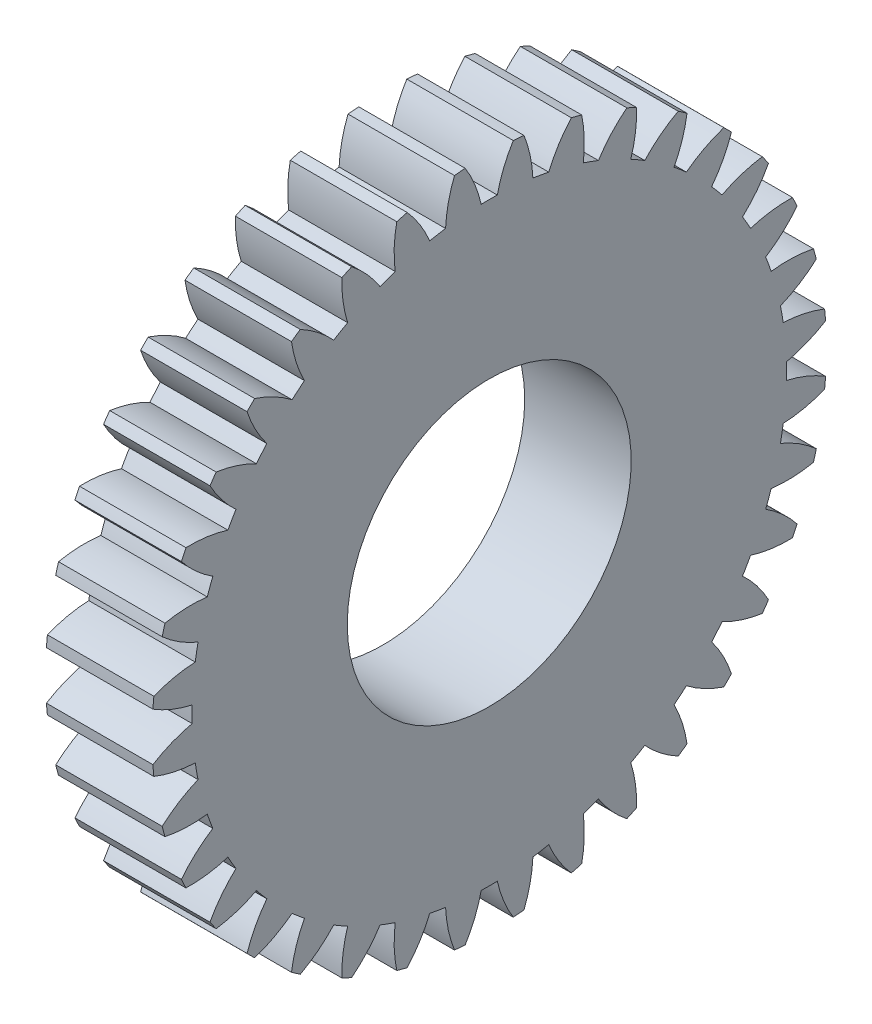
SolidWorks part; units mm, degrees
ref_plane "Plane1" through (0, 0, 0) normal (0, 0, 1) x (1, 0, 0)
ref_plane "Plane2" through (0, 0, 0) normal (0, 1, 0) x (1, 0, 0)
ref_plane "Plane3" through (0, 0, 0) normal (1, 0, 0) x (0, 0, -1)
sketch "HoldingSke" plane through (0, 0, 0) normal (0, 1, 0) x (1, 0, 0)
  line L0 (0, 0) -> (1.618, -1.1756)
  line L1 (-15, 0) -> (100, 0) construction
  line L2 (0, 0) -> (-2.1039, 2.3779)
  line L3 (0, 0) -> (-11.863, 4.5341)
  line L4 (0, 0) -> (6.9867, 5.0761)
  line L5 (0, 0) -> (-46.8476, -17.4728)
  line L6 (0, 0) -> (-2.4869, -1.6779)
  line L7 (-2.1039, 2.3779) -> (8.6586, 51.2059)
  line L8 (-76.2, 54.61) -> (-74.8, 54.61)
  line L9 (-71.009, 38.7566) -> (-53.1078, 45.2721)
  line L10 (-76.2, 71.12) -> (104.1128, 71.12)
  line L11 (0, 0) -> (-3, 0)
  line L12 (-76.2, 101.6) -> (-76.181, 101.6)
  line L13 (24.9733, 27.94) -> (52.9518, 28.4284)
  line L14 (24.9733, 27.94) -> (24.9743, 27.94)
  line L15 (24.9733, 27.94) -> (100.4006, 29.5858)
  line L16 (-63.627, -0.5) -> (-12.827, -0.5)
  circle A0 centre (0, 0) radius 4.5
  circle A1 centre (0, 0) radius 8.374
  circle A2 centre (0, 0) radius 37.5
  circle A3 centre (0, 0) radius 4.5
  dimension "MHD" = 16.748
  dimension "Hub_dia" = 75
  dimension "Bore" = 9
  dimension "MBD" = 9
  dimension "Num_teeth" = 36
  dimension "Pitch" = 2
  dimension "Overall_len" = 50
  dimension "Show_teeth" = 36
  dimension "Thickness" = 3
  dimension "OAL" = 50.0001
  dimension "T_dim" = 1.4
  dimension "Ap" = 20
  dimension "H" = 19.05
  dimension "Pitch_radius" = 180.3128
  dimension "Width" = 3
  dimension "Backlash" = 0.019
  dimension "Addendum_fac" = 1
  dimension "Dedendum_fac" = 1.25
  dimension "Clearance_fac" = 0.25
  dimension "Dedendum_add" = 0.001
  dimension "Module" = 0.5
sketch "BasProSke" plane through (0, 0, 0) normal (0, 1, 0) x (1, 0, 0)
  line L0 (-10, 0) -> (60, 0) construction
  line L1 (0, 0) -> (0, 9.5)
  line L2 (0, 0) -> (3, 0)
  line L3 (3, 0) -> (3, 9.5)
  line L4 (3, 9.5) -> (0, 9.5)
  dimension "Thickness" = 3
  dimension "Diameter" = 19
revolve "Base-Revolve" add sketch "BasProSke" angle 360 about L0
sketch "TooCutSke" plane through (0, 0, 0) normal (1, 0, 0) x (0, 0, -1)
  line L1 (0, 0) -> (0, 107) construction
  line L2 (0, 0) -> (-0.4258, 8.9899) construction
  line L3 (0, 0) -> (-1.5676, 17.9172) construction
  line L4 (-0.4258, 8.9899) -> (-0.7838, 8.9586) construction
  arc A0 (0.2272, 8.3709) -> (-0.2272, 8.3709) centre (0, 0) ccw
  arc A1 (0.6921, 9.5002) -> (-0.6921, 9.5002) centre (0, 0) ccw
  circle A2 centre (0, 0) radius 9 construction
  circle A3 centre (0, 0) radius 8.4572 construction
  arc A4 (-0.2272, 8.3709) -> (-0.6921, 9.5002) centre (-3.7404, 7.5851) ccw
  arc A5 (0.6921, 9.5002) -> (0.2272, 8.3709) centre (3.7404, 7.5851) ccw
  dimension "Root_dia" = 16.748
  dimension "Overcut_dia" = 19.0508
  dimension "Pitch_dia" = 18
  dimension "Base_dia" = 16.9145
  dimension "Flank_rad" = 3.6
  dimension "Half_ang" = 5
  dimension "Half_CT" = 0.3593
extrude "ToothCut" cut sketch "TooCutSke" along normal through all
fillet "Breaks" [suppressed] radius 0.01
fillet "RootFillets" [suppressed] radius 0.126
pattern_circular "TeethCuts" count 36 every 10 about axis through (-10, 0, 0) along (1, 0, 0) of "ToothCut", "RootFillets", "Breaks"
sketch "HubNeaOneSke" plane through (0, 0, 0) normal (-1, 0, 0) x (0, 0, 1)
  circle A0 centre (0, 0) radius 8.374
  dimension "Diameter" = 16.748
extrude "HubNearOne" [suppressed] add sketch "HubNeaOneSke" along normal blind 47.0001
sketch "HubNeaBotSke" plane through (0, 0, 0) normal (-1, 0, 0) x (0, 0, 1)
  circle A0 centre (0, 0) radius 8.374
  dimension "Diameter" = 16.748
extrude "HubNearBoth" [suppressed] add sketch "HubNeaBotSke" along normal blind 23.5
ref_plane "FarPln" through (3, 0, 0) normal (1, 0, 0) x (0, 0, -1)
sketch "HubFarSke" plane through (3, 0, 0) normal (1, 0, 0) x (0, 0, -1)
  circle A0 centre (0, 0) radius 8.374
  dimension "Diameter" = 16.748
extrude "HubFar" [suppressed] add sketch "HubFarSke" along normal blind 23.5
sketch "BorSke" plane through (0, 0, 0) normal (1, 0, 0) x (0, 0, -1)
  circle A0 centre (0, 0) radius 4
  dimension "Diameter" = 8
extrude "Bore" cut sketch "BorSke" along normal mid plane 100.0001
sketch "KeySke" plane through (0, 0, 0) normal (1, 0, 0) x (0, 0, -1)
  line L0 (-1.5, 0) -> (-1.5, 5.9)
  line L1 (-1.5, 5.9) -> (1.5, 5.9)
  line L2 (1.5, 5.9) -> (1.5, 0)
  line L3 (0, 0) -> (0, 34) construction
  line L4 (-1.5, 0) -> (1.5, 0)
  dimension "Width" = 3
  dimension "Offset" = 5.9
extrude "Keyway" [suppressed] cut sketch "KeySke" along normal mid plane 100.0001
pattern_circular "Keyway2" [suppressed] count 2 every 90 about axis through (-10, 0, 0) along (1, 0, 0)
equation "' \"Module@HoldingSke\" = 6.35"
equation "' \"Num_teeth@HoldingSke\" = 12"
equation "' \"Ap@HoldingSke\" =  20"
equation "' \"Ap@HoldingSke\" = 20"
equation "' \"Width@HoldingSke\" = 0.5 * 25.4"
equation "' \"Hub_dia@HoldingSke\"= 1 * 25.4"
equation "' \"Hub_dia@HoldingSke\" = 1 * 25.4"
equation "' \"Overall_len@HoldingSke\" = 1.0 * 25.4"
equation "' \"Bore@HoldingSke\" = 0.75 * 25.4"
equation "' \"T_dim@HoldingSke\" = 0.1 * 25.4"
equation "' \"Width@KeySke\" = 0.25 * 25.4"
equation "' \"Show_teeth@HoldingSke\" = 13"
equation "' \"Backlash@HoldingSke\" = 0.009 * 25.4"
equation "' \"Addendum_fac@HoldingSke\" = 1.0"
equation "' \"Dedendum_fac@HoldingSke\" = 1.25"
equation "' \"Dedendum_add@HoldingSke\" = 0.00005 * 25.4"
equation "' \"Clearance_fac@HoldingSke\" = 0.25"
equation "\"Pitch@HoldingSke\" = 1 / \"Module@HoldingSke\""
equation "\"Overcut_dia@TooCutSke\" = (\"Num_teeth@HoldingSke\" + 2 * \"Addendum_fac@HoldingSke\") / \"Pitch@HoldingSke\" + 0.002 * 25.4"
equation "\"Pitch_dia@TooCutSke\" = \"Num_teeth@HoldingSke\" / \"Pitch@HoldingSke\""
equation "\"Base_dia@TooCutSke\" = \"Num_teeth@HoldingSke\" / \"Pitch@HoldingSke\" * cos((\"Ap@HoldingSke\"  * 3.14159265 / 180))"
equation "\"Root_dia@TooCutSke\" = (\"Num_teeth@HoldingSke\" + 2) / \"Pitch@HoldingSke\" - 2 * (\"Addendum_fac@HoldingSke\" + \"Dedendum_fac@HoldingSke\") / \"Pitch@HoldingSke\" - \"Dedendum_add@HoldingSke\" * 2"
equation "\"Half_ang@TooCutSke\" = 180 / \"Num_teeth@HoldingSke\""
equation "\"Half_CT@TooCutSke\" = \"Num_teeth@HoldingSke\" / \"Pitch@HoldingSke\" * sin((3.14159265 / 2 / \"Num_teeth@HoldingSke\")) / 2 - 7 * \"Backlash@HoldingSke\" / 4"
equation "\"Flank_rad@TooCutSke\" = \"Num_teeth@HoldingSke\" / \"Pitch@HoldingSke\" / 5"
equation "\"Radius@RootFillets\" = \"Clearance_fac@HoldingSke\" / \"Pitch@HoldingSke\" + \"Dedendum_add@HoldingSke\""
equation "\"Break_rad@Breaks\" = 0.02 / \"Pitch@HoldingSke\""
equation "\"Thickness@HoldingSke\" = \"Width@HoldingSke\""
equation "\"OAL@HoldingSke\" = \"Thickness@HoldingSke\""
equation "\"MHD@HoldingSke\" = (\"Num_teeth@HoldingSke\" + 2) / \"Pitch@HoldingSke\" - 2 * (\"Addendum_fac@HoldingSke\" + \"Dedendum_fac@HoldingSke\")  / \"Pitch@HoldingSke\" - \"Dedendum_add@HoldingSke\" * 2"
equation "\"MBD@HoldingSke\" = (\"Num_teeth@HoldingSke\" + 2) / \"Pitch@HoldingSke\" - 2 * (\"Addendum_fac@HoldingSke\" + \"Dedendum_fac@HoldingSke\")  / \"Pitch@HoldingSke\" - \"Dedendum_add@HoldingSke\" * 2 - 0.002 * 25.4"
equation "\"MHD@HoldingSke\" = ((sgn( \"MHD@HoldingSke\" - \"Hub_dia@HoldingSke\" )-1)*( \"MHD@HoldingSke\" - \"Hub_dia@HoldingSke\" ))/-2+ \"Hub_dia@HoldingSke\""
equation "\"MBD@HoldingSke\" = ((sgn( \"MBD@HoldingSke\" - \"Bore@HoldingSke\" )-1)*( \"MBD@HoldingSke\" - \"Bore@HoldingSke\" ))/-2+ \"Bore@HoldingSke\""
equation "\"OAL@HoldingSke\" = ((sgn( \"OAL@HoldingSke\" - \"Overall_len@HoldingSke\" )+1)*( \"OAL@HoldingSke\" - \"Overall_len@HoldingSke\" ))/2 + \"Overall_len@HoldingSke\" + 0.000002 * 25.4"
equation "\"Num_teeth@TeethCuts\" = int( \"Show_teeth@HoldingSke\" ) + 1"
equation "\"Num_teeth@TeethCuts\" = ((sgn( \"Num_teeth@TeethCuts\" - \"Num_teeth@HoldingSke\" )-1)*( \"Num_teeth@TeethCuts\" - \"Num_teeth@HoldingSke\" ))/-2+ \"Num_teeth@HoldingSke\""
equation "\"Num_teeth@TeethCuts\" = ((sgn( \"Num_teeth@TeethCuts\" - 2.0)+1)*( \"Num_teeth@TeethCuts\" - 2.0))/2 +2.0"
equation "\"Angle@TeethCuts\" = 360.0 / \"Num_teeth@HoldingSke\""
equation "\"Diameter@BasProSke\" = (\"Num_teeth@HoldingSke\" + 2 * \"Addendum_fac@HoldingSke\") / \"Pitch@HoldingSke\""
equation "\"Thickness@BasProSke\"  = \"Thickness@HoldingSke\""
equation "' \"Fillet_rad@BasProSke\" =  \"Thickness@HoldingSke\" * 0.05"
equation "' \"Fillet_rad@BasProSke\" = \"Thickness@HoldingSke\" * 0.05"
equation "\"MHD@HoldingSke\" = ((sgn( \"MHD@HoldingSke\" - \"Root_dia@TooCutSke\" )-1)*( \"MHD@HoldingSke\" - \"Root_dia@TooCutSke\" ))/-2+ \"Root_dia@TooCutSke\""
equation "\"Diameter@HubNeaOneSke\" = \"MHD@HoldingSke\""
equation "\"Length@HubNearOne\" = \"OAL@HoldingSke\" - \"Thickness@BasProSke\""
equation "\"Diameter@HubNeaBotSke\" = \"MHD@HoldingSke\""
equation "\"Length@HubNearBoth\" = ( \"OAL@HoldingSke\" - \"Thickness@BasProSke\" ) / 2.0"
equation "\"Thickness@FarPln\" = \"Thickness@BasProSke\""
equation "\"Diameter@HubFarSke\" = \"MHD@HoldingSke\""
equation "\"Length@HubFar\" = ( \"OAL@HoldingSke\" - \"Thickness@BasProSke\" ) / 2.0"
equation "\"Diameter@BorSke\"=8"
equation "\"D1@Bore\" = \"OAL@HoldingSke\" * 2.0"
equation "\"D1@Keyway\" = \"OAL@HoldingSke\" * 2.0"
equation "\"Offset@KeySke\" = \"T_dim@HoldingSke\" + \"MBD@HoldingSke\" / 2.0"
